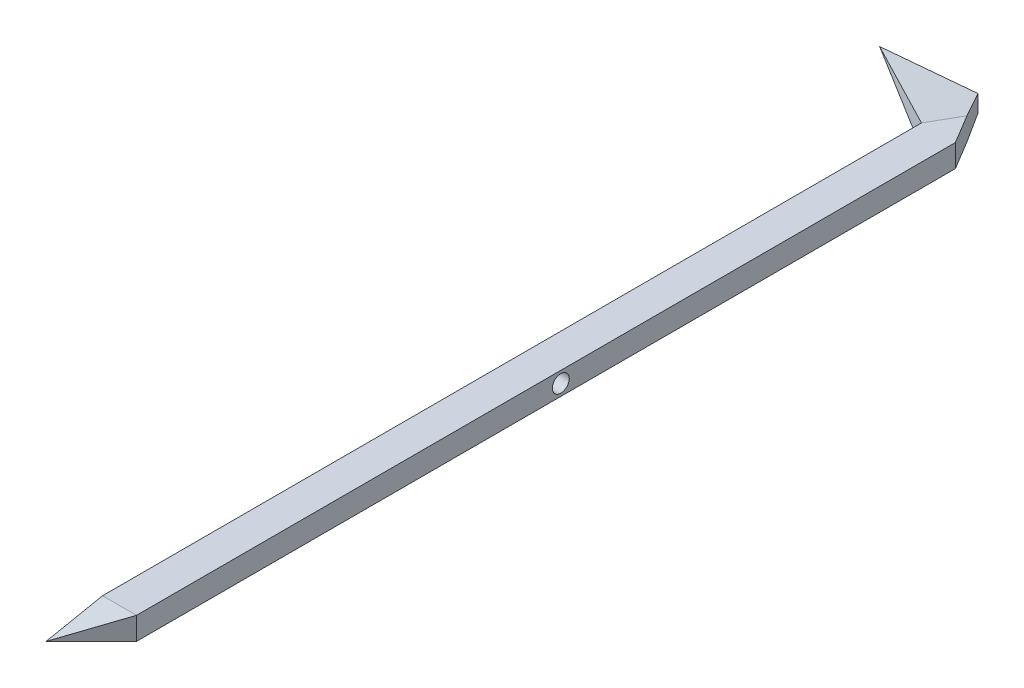
SolidWorks part; units mm, degrees
ref_plane "Front Plane" through (0, 0, 0) normal (0, 0, 1) x (1, 0, 0)
ref_plane "Top Plane" through (0, 0, 0) normal (0, 1, 0) x (1, 0, 0)
ref_plane "Right Plane" through (0, 0, 0) normal (1, 0, 0) x (0, 0, -1)
sketch "Sketch1" plane through (0, 0, 0) normal (0, 1, 0) x (1, 0, 0)
  line L0 (0, 104.6861) -> (0, -104.6861)
  line L1 (0, -104.6861) -> (7.62, -91.9861)
  line L2 (7.62, -91.9861) -> (7.62, 91.9861)
  line L3 (7.62, 91.9861) -> (0, 104.6861)
  line L4 (0, 104.6861) -> (-22.098, 104.6861)
  line L5 (-22.098, 104.6861) -> (0, 91.9861)
  line L6 (0, 91.9861) -> (0, 104.6861)
  line L7 (0, 3.3401) -> (-25.4, 3.3401)
  line L8 (7.62, 3.3401) -> (33.02, 3.3401)
  point P4 (0, 0)
  dimension "D1" = 209.3722
  dimension "D2" = 12.7
  dimension "D3" = 12.7
  dimension "D4" = 7.62
  dimension "D5" = 22.098
  dimension "D6" = 101.346
  dimension "D7" = 25.4
  dimension "D8" = 25.4
extrude "Boss-Extrude1" add sketch "Sketch1" along normal blind 5.08 contours L2 L3 L0 L1 | L4 L5 L0
sketch "Sketch2" plane through (7.62, 0, 0) normal (1, 0, 0) x (0, 0, -1)
  line L0 (-91.9861, 5.08) -> (-104.6861, 2.54)
  line L1 (-104.6861, 5.08) -> (-104.6861, 0) construction
  line L2 (-104.6861, 2.54) -> (-91.9861, 0)
  line L3 (-91.9861, 0) -> (-104.6861, 0)
  line L4 (-104.6861, 0) -> (-104.6861, 2.54)
  line L5 (-104.6861, 5.08) -> (-91.9861, 5.08)
  line L6 (-104.6861, 5.08) -> (-104.6861, 2.54)
extrude "Cut-Extrude1" cut sketch "Sketch2" along normal through all both and the other way through all contours L5 L6 L0 | L4 L3 L2
sketch "Sketch3" plane through (39.7397, 0, -69.1472) normal (-0.4983, 0, 0.867) x (0.867, 0, 0.4983)
  line L0 (-45.8352, 5.08) -> (-71.3227, 2.54)
  line L1 (-71.3227, 5.08) -> (-71.3227, 0) construction
  line L2 (-71.3227, 2.54) -> (-45.8352, 0)
  line L3 (-45.8352, 0) -> (-71.3227, 0)
  line L4 (-71.3227, 0) -> (-71.3227, 2.54)
  line L5 (-45.8352, 5.08) -> (-71.3227, 5.08)
  line L6 (-71.3227, 5.08) -> (-71.3227, 2.54)
  line M1 (-71.3227, 0) -> (-45.8352, 0)
  line M3 (-45.8352, 5.08) -> (-71.3227, 5.08)
  line M4 (-71.3227, 5.08) -> (-71.3227, 0)
extrude "Cut-Extrude2" cut sketch "Sketch3" against normal through all both and the other way through all contours L0 M3 M4 | L2 M4 M1
sketch "Sketch4" plane through (0, 0, 0) normal (-1, 0, 0) x (0, 0, 1)
  circle A0 centre (-3.3401, 2.54) radius 1.905
  point P2 (0, 0)
  point P6 (0, 0)
  dimension "D2" = 3.81
  dimension "D1" = 101.346
extrude "Cut-Extrude3" cut sketch "Sketch4" against normal blind 21.336
